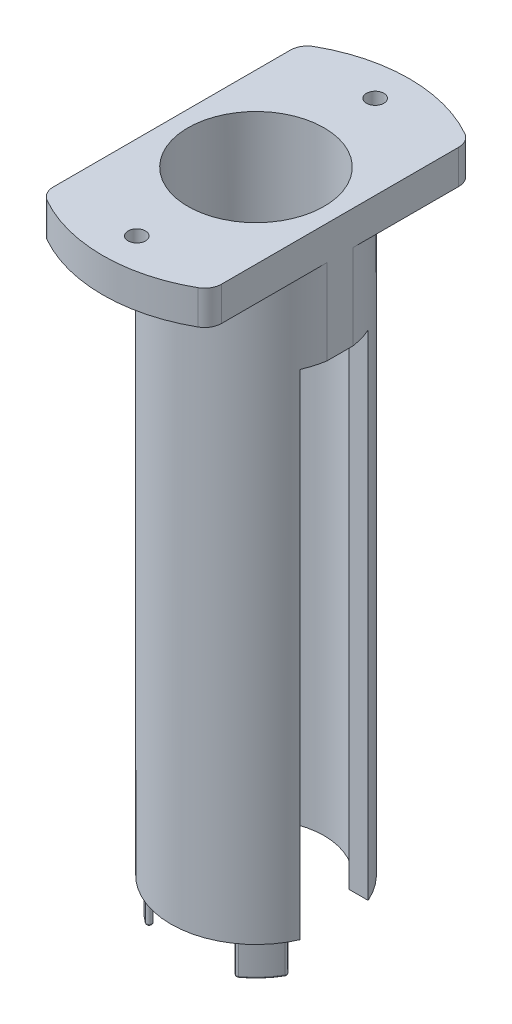
SolidWorks part; units mm, degrees
material "ABS"
ref_plane "前视" through (0, 0, 0) normal (0, 0, 1) x (1, 0, 0)
ref_plane "上视" through (0, 0, 0) normal (0, 1, 0) x (1, 0, 0)
ref_plane "右视" through (0, 0, 0) normal (1, 0, 0) x (0, 0, -1)
sketch "草图3" plane through (0, 0, 0) normal (0, 1, 0) x (1, 0, 0)
  circle A0 centre (0, 0) radius 25
  dimension "D1" = 50
extrude "凸台-拉伸1" add sketch "草图3" along normal blind 340
sketch "草图6" plane through (0, 0, 0) normal (0, -1, 0) x (1, 0, 0)
  circle A0 centre (0, 0) radius 45
  circle A1 centre (0, 0) radius 25 construction
  dimension "D1" = 20
extrude "凸台-拉伸2" add sketch "草图6" along normal blind 10
sketch "草图7" plane through (0, 340, 0) normal (0, 1, 0) x (1, 0, 0)
  circle A0 centre (0, 0) radius 45
extrude "凸台-拉伸3" add sketch "草图7" along normal blind 10
sketch "草图4" plane through (0, -10, 0) normal (0, -1, 0) x (1, 0, 0)
  circle A0 centre (0, 0) radius 20
  dimension "D1" = 40
extrude "切除-拉伸1" cut sketch "草图4" against normal through all
sketch "草图8" plane through (0, 350, 0) normal (0, 1, 0) x (1, 0, 0)
  line L0 (24.704, -37.6127) -> (24.704, 37.6127)
  line L1 (24.704, -37.6127) -> (65.296, -37.6127)
  line L2 (24.704, 37.6127) -> (65.296, 37.6127)
  line L3 (65.296, -37.6127) -> (65.296, 37.6127)
  line L4 (24.704, -37.6127) -> (65.296, 37.6127) construction
  line L5 (24.704, 37.6127) -> (65.296, -37.6127) construction
  circle A0 centre (0, 0) radius 45 construction
  point P1 (45, 0)
extrude "切除-拉伸2" cut sketch "草图8" against normal through all
ref_plane "基准面1" through (-25.296, 0, 0) normal (1, 0, 0) x (0, 0, -1)
sketch "草图9" plane through (-25.296, 0, 0) normal (1, 0, 0) x (0, 0, -1)
  line L0 (-45, -10) -> (45, -10) construction
  line L1 (10, 315) -> (-10, 315)
  line L2 (10, 315) -> (10, 25)
  line L3 (10, 25) -> (-10, 25)
  line L4 (-10, 315) -> (-10, 25)
  line L5 (10, 315) -> (-10, 25) construction
  line L6 (10, 25) -> (-10, 315) construction
  line L11 (45, 350) -> (-45, 350) construction
  point P0 (0, 170)
  dimension "D1" = 35
  dimension "D2" = 35
  dimension "D3" = 20
  dimension "D4" = 10
extrude "切除-拉伸3" cut sketch "草图9" along normal through all
hole_wizard "M6x1.0 螺纹孔1" positions "草图10" profile "草图11" tap size "M6x1.0" standard "ANSI Metric" end condition through all
sketch "草图10" plane through (0, 350, 0) normal (0, 1, 0) x (1, 0, 0)
  point P0 (0, -35)
  point P2 (0, 35)
  dimension "D1" = 35
  dimension "D2" = 35
sketch "草图11" plane through (0, 350, 35) normal (1, 0, 0) x (0, 0, 1)
  line L0 (0, 0) -> (0, 360)
  line L1 (0, 360) -> (2.5, 360)
  line L2 (2.5, 360) -> (2.5, 0)
  line L5 (2.5, 0) -> (0, 0)
  line L11 (0, -6.35) -> (0, 107.95) construction
  dimension "通孔螺纹孔钻头直径" = 5
  dimension "通孔螺纹孔钻头深度" = 360
cosmetic thread "孔螺蚊线1" parameters "D2"=6
cosmetic thread "孔螺蚊线2" parameters "D2"=6
mirror "镜向1" about plane through (0, 0, 0) normal (1, 0, 0) of "切除-拉伸2"
fillet "圆角1" radius 5 8 edges at (-24.704, 345, 37.6127) (-24.704, 345, -37.6127) (-24.704, -5, -37.6127) (-24.704, -5, 37.6127) (24.704, -5, -37.6127) (24.704, -5, 37.6127) (24.704, 345, -37.6127) (24.704, 345, 37.6127)
sketch "草图12" plane through (0, 350, 0) normal (0, 1, 0) x (1, 0, 0)
  circle A0 centre (0, 35) radius 2.55
  circle A2 centre (0, -35) radius 2.55
  dimension "D1" = 5.1
  dimension "D2" = 5.1
extrude "切除-拉伸4" cut sketch "草图12" against normal through all
sketch "草图13" plane through (0, -10, 0) normal (0, -1, 0) x (1, 0, 0)
  line L1 (-144.258, -179.1959) -> (101.4888, -179.1959)
  line L2 (-144.258, -179.1959) -> (-144.258, 155.8258)
  line L3 (-144.258, 155.8258) -> (101.4888, 155.8258)
  line L4 (101.4888, -179.1959) -> (101.4888, 155.8258)
extrude "切除-拉伸5" cut sketch "草图13" against normal blind 180
sketch "草图16" plane through (0, 170, 0) normal (0, -1, 0) x (1, 0, 0)
  line L0 (-17.3205, -10) -> (-22.9129, -10) construction
  line L1 (22.9129, -10) -> (17.3205, -10) construction
  line L2 (-6.1476, 0) -> (6.8222, 0) construction
  arc A0 (-20.1167, -10) -> (20.1167, -10) centre (0, 0) ccw
  arc A1 (-19.4554, -11.2326) -> (-13.2047, -18.1747) centre (0, 0) ccw construction
  arc A2 (-20.3214, -11.7326) -> (-13.7924, -18.9837) centre (0, 0) ccw
  arc A3 (-18.5893, -10.7326) -> (-12.6169, -17.3656) centre (0, 0) ccw
  arc A4 (-18.5893, -10.7326) -> (-20.3214, -11.7326) centre (-19.4554, -11.2326) ccw
  arc A5 (-13.7924, -18.9837) -> (-12.6169, -17.3656) centre (-13.2047, -18.1747) ccw
  arc A6 (19.4554, -11.2326) -> (13.2047, -18.1747) centre (0, 0) cw construction
  arc A7 (13.7924, -18.9837) -> (20.3214, -11.7326) centre (0, 0) ccw
  arc A8 (12.6169, -17.3656) -> (18.5893, -10.7326) centre (0, 0) ccw
  arc A9 (12.6169, -17.3656) -> (13.7924, -18.9837) centre (13.2047, -18.1747) ccw
  arc A10 (20.3214, -11.7326) -> (18.5893, -10.7326) centre (19.4554, -11.2326) ccw
  point P13 (-16.6948, -15.0321)
  point P18 (16.6948, -15.0321)
  dimension "D4" = 1
  dimension "D5" = 1
  dimension "D1" = 120
  dimension "D2" = 24
  dimension "D3" = 24
extrude "切除-拉伸7" cut sketch "草图16" against normal blind 30 contours A2 A5 A3 A4 | A7 A10 A8 A9
sketch "草图17" plane through (0, 170, 0) normal (0, -1, 0) x (1, 0, 0)
  line L0 (6.1476, 0) -> (-6.8222, 0) construction
  arc A1 (19.4554, 11.2326) -> (13.2047, 18.1747) centre (0, 0) ccw construction
  arc A2 (20.1482, 11.6326) -> (13.6749, 18.8219) centre (0, 0) ccw
  arc A3 (18.7625, 10.8326) -> (12.7344, 17.5274) centre (0, 0) ccw
  arc A4 (18.7625, 10.8326) -> (20.1482, 11.6326) centre (19.4554, 11.2326) ccw
  arc A5 (13.6749, 18.8219) -> (12.7344, 17.5274) centre (13.2047, 18.1747) ccw
  arc A6 (-19.4554, 11.2326) -> (-13.2047, 18.1747) centre (0, 0) cw construction
  arc A7 (-13.6749, 18.8219) -> (-20.1482, 11.6326) centre (0, 0) ccw
  arc A8 (-12.7344, 17.5274) -> (-18.7625, 10.8326) centre (0, 0) ccw
  arc A9 (-12.7344, 17.5274) -> (-13.6749, 18.8219) centre (-13.2047, 18.1747) ccw
  arc A10 (-20.1482, 11.6326) -> (-18.7625, 10.8326) centre (-19.4554, 11.2326) ccw
  point P10 (16.6948, 15.0321)
  point P15 (-16.6948, 15.0321)
  dimension "D1" = 0.8
  dimension "D2" = 0.8
extrude "凸台-拉伸4" add sketch "草图17" along normal blind 10
fillet "圆角5" radius 0.5 4 edges at (-12.5574, 160, 18.6449) (-17.2893, 160, 15.5674) (-19.8554, 160, 10.5397) (-16.1003, 160, 14.4968)
fillet "圆角6" radius 0.5 4 edges at (19.8554, 160, 10.5397) (17.2893, 160, 15.5674) (12.5574, 160, 18.6449) (16.1003, 160, 14.4968)
